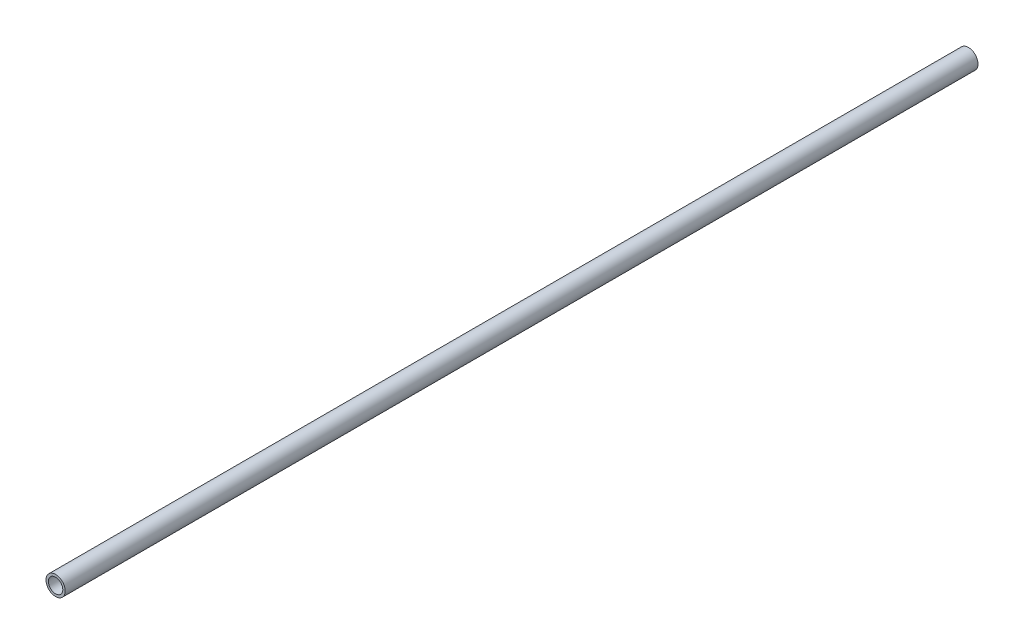
SolidWorks part; units mm, degrees
ref_plane "Спереди" through (0, 0, 0) normal (0, 0, 1) x (1, 0, 0)
ref_plane "Сверху" through (0, 0, 0) normal (0, 1, 0) x (1, 0, 0)
ref_plane "Справа" through (0, 0, 0) normal (1, 0, 0) x (0, 0, -1)
sketch "Эскиз1" plane through (0, 0, 0) normal (0, 0, 1) x (1, 0, 0)
  circle A0 centre (0, 0) radius 4
  circle A1 centre (0, 0) radius 3
extrude "Бобышка-Вытянуть1" add sketch "Эскиз1" along normal blind 380
